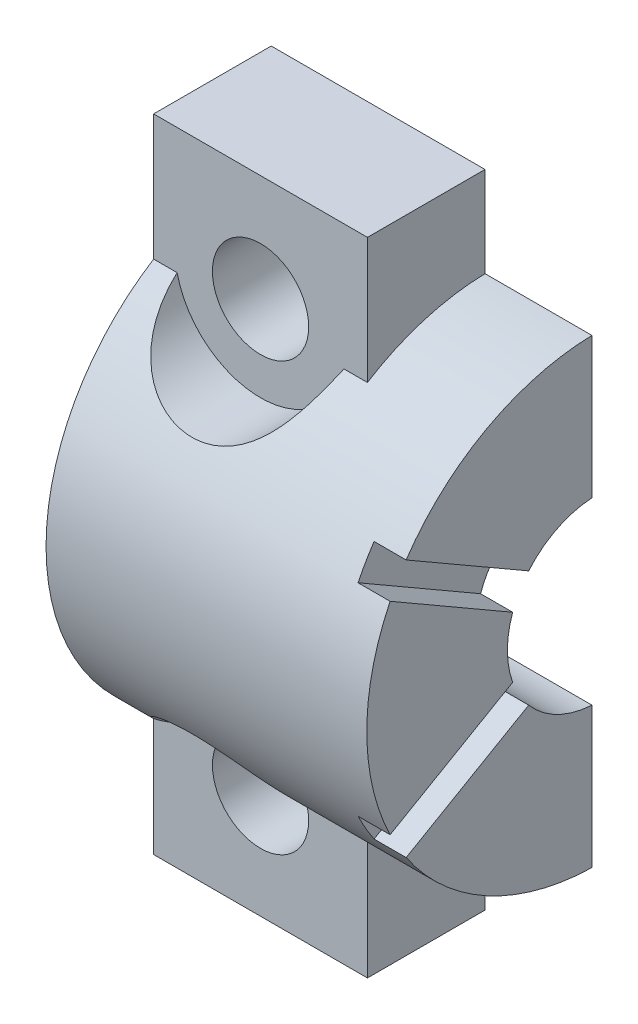
SolidWorks part; units mm, degrees
ref_plane "Front Plane" through (0, 0, 0) normal (0, 0, 1) x (1, 0, 0)
ref_plane "Top Plane" through (0, 0, 0) normal (0, 1, 0) x (1, 0, 0)
ref_plane "Right Plane" through (0, 0, 0) normal (1, 0, 0) x (0, 0, -1)
sketch "Sketch1" plane through (0, 0, 0) normal (0, 0, 1) x (1, 0, 0)
  line L1 (-5, -15) -> (5, -15)
  line L2 (-5, -15) -> (-5, 15)
  line L3 (-5, 15) -> (5, 15)
  line L4 (5, -15) -> (5, 15)
  line L5 (-5, -15) -> (5, 15) construction
  line L6 (-5, 15) -> (5, -15) construction
  point P1 (0, 0)
  dimension "D1" = 10
  dimension "D2" = 30
extrude "Boss-Extrude1" add sketch "Sketch1" along normal blind 5.5
sketch "Sketch2" plane through (5, 0, 0) normal (1, 0, 0) x (0, 0, -1)
  circle A0 centre (0.25, 0) radius 4.205
  dimension "D1" = 8.41
  dimension "D2" = 0.25
extrude "Cut-Extrude1" cut sketch "Sketch2" against normal through all
sketch "Sketch9" plane through (5, 0, 0) normal (1, 0, 0) x (0, 0, -1)
  line L5 (0, -15) -> (0, -4.1976)
  line L6 (0, 4.1976) -> (0, 15)
  line L7 (0, 15) -> (-5.5, 15)
  line L8 (-5.5, 15) -> (-5.5, -15)
  line L9 (-5.5, -15) -> (0, -15)
  line L10 (0, -10.7784) -> (0, -4.1976)
  line L11 (0, 4.1976) -> (0, 10.7784)
  line L13 (-5.5, 9.1199) -> (-5.5, -9.1199)
  arc A0 (0, 10.7784) -> (0, -10.7784) centre (0.25, 0) ccw
  arc A2 (0, 4.1976) -> (0, -4.1976) centre (0.25, 0) ccw
  arc A3 (0, 4.1976) -> (0, -4.1976) centre (0.25, 0) ccw
  dimension "D1" = 21.5625
  dimension "D2" = 0
extrude "Boss-Extrude2" add sketch "Sketch9" along normal blind 5 and the other way up to surface contours L7 A0 L9 L5 L6 | L9 A0
sketch "Sketch12" plane through (10, 0, 0) normal (1, 0, 0) x (0, 0, -1)
  line L0 (0.25, 0) -> (-9.0868, -5.3906)
  arc A0 (0, 4.1976) -> (0, -4.1976) centre (0.25, 0) ccw construction
  arc A1 (0, 4.1976) -> (0, -4.1976) centre (0.25, 0) ccw construction
  arc A2 (0, 10.7784) -> (0, -10.7784) centre (0.25, 0) ccw construction
  dimension "D1" = 30
extrude "Cut-Extrude-Thin1" cut sketch "Sketch12" against normal blind 1.5 and the other way through all thin thin type mid plane wall 1.5
sketch "Sketch21" plane through (10, 0, 0) normal (1, 0, 0) x (0, 0, -1)
  line L0 (0.25, 0) -> (-9.0868, 5.3906)
  arc A0 (0, 10.7784) -> (-9.4392, -4.7281) centre (0.25, 0) ccw construction
  dimension "D1" = 30
extrude "Cut-Extrude-Thin2" cut sketch "Sketch21" against normal blind 1.5 and the other way through all thin thin type mid plane wall 1.5
ref_plane "Plane2" through (0, 0, 10.5313) normal (0, 0, 1) x (1, 0, 0)
hole_wizard "CBORE for M4 SHCS1" positions "Sketch20" profile "Sketch19" counterbore size "M4" standard "ANSI Metric" end condition through all
sketch "Sketch20" plane through (0, 0, 10.5313) normal (0, 0, 1) x (1, 0, 0)
  line L0 (-5, -15) -> (5, -15) construction
  line L1 (5, 15) -> (-5, 15) construction
  point P0 (0, 10)
  point P2 (0, -10)
  dimension "D1" = 5
  dimension "D2" = 5
sketch "Sketch19" plane through (0, 10, 10.5313) normal (1, 0, 0) x (0, -1, 0)
  line L0 (0, 0) -> (0, 10.5313)
  line L1 (0, 10.5313) -> (2.25, 10.5313)
  line L3 (2.25, 10.5313) -> (2.25, 4)
  line L4 (2.25, 4) -> (4, 4)
  line L5 (4, 4) -> (4, 0)
  line L7 (4, 0) -> (0, 0)
  line L11 (0, -6.35) -> (0, 107.95) construction
  dimension "Thru Hole Dia." = 4.5
  dimension "Thru Hole Depth" = 10.5313
  dimension "C'Bore Dia." = 8
  dimension "C'Bore Depth" = 4
sketch "Sketch22" plane through (0, 0, 6.5313) normal (0, 0, 1) x (1, 0, 0)
  line L2 (3.6579, 8.3815) -> (1.563, 8.3815)
  line L3 (-1.563, 8.3815) -> (-3.6579, 8.3815)
  line L6 (-3.6579, -8.3815) -> (-1.563, -8.3815)
  line L7 (1.563, -8.3815) -> (3.6579, -8.3815)
  arc A2 (-1.563, 8.3815) -> (1.563, 8.3815) centre (0, 10) ccw
  arc A3 (-3.6579, 8.3815) -> (3.6579, 8.3815) centre (0, 10) ccw
  circle A5 centre (0, 10) radius 4
  arc A6 (1.563, -8.3815) -> (-1.563, -8.3815) centre (0, -10) ccw
  arc A7 (3.6579, -8.3815) -> (-3.6579, -8.3815) centre (0, -10) ccw
  circle A9 centre (0, -10) radius 4
  point P7 (-3.6579, 8.6055)
  point P10 (3.6579, -8.6051)
  dimension "D1" = 0
  dimension "D2" = 0
extrude "Cut-Extrude2" cut sketch "Sketch22" against normal up to surface (1.0313 mm away) up to face at (0, 11.6016, 5.5)
